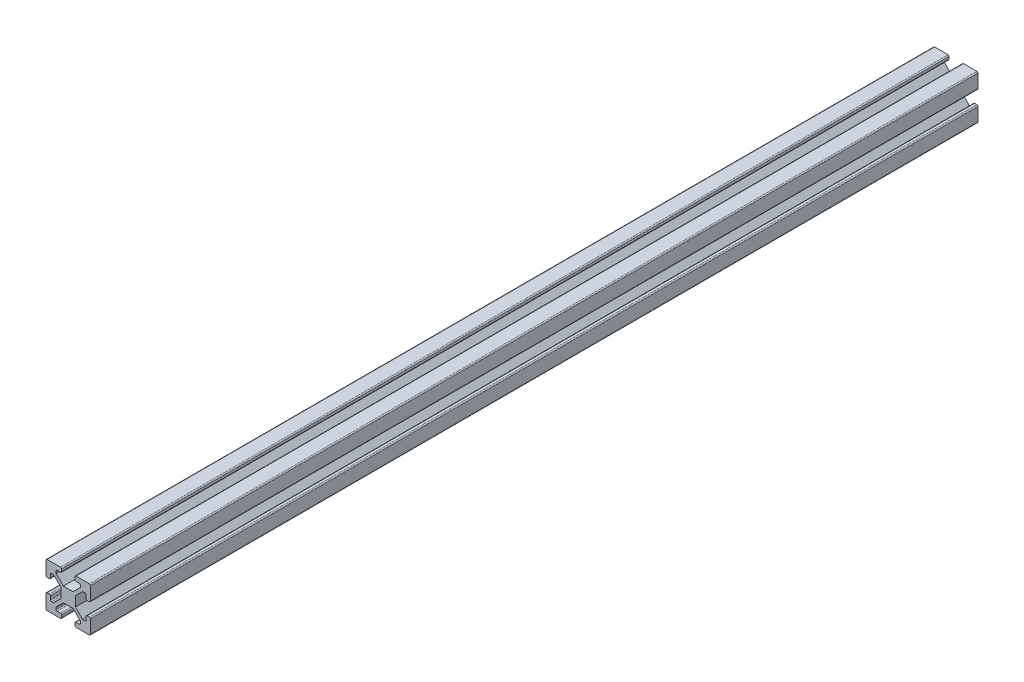
SolidWorks part; units mm, degrees
material "3.1645 (EN AW-2007)"
ref_plane "Front" through (0, 0, 0) normal (0, 0, 1) x (1, 0, 0)
ref_plane "Top" through (0, 0, 0) normal (0, 1, 0) x (1, 0, 0)
ref_plane "Right" through (0, 0, 0) normal (1, 0, 0) x (0, 0, -1)
sketch "草图1" plane through (0, 0, 0) normal (0, 0, 1) x (1, 0, 0)
  line L0 (6.5, 0) -> (0.5, 0)
  line L1 (20, -0.5) -> (20, -6.5)
  line L2 (19.5, -20) -> (13.5, -20)
  line L3 (20, -13.5) -> (20, -19.5)
  line L4 (13, -19.5) -> (13, -18.5)
  line L5 (13.5, -18) -> (15, -18)
  line L6 (15.5, -17.5) -> (15.5, -16.7791)
  line L7 (19.5, -7) -> (18.5, -7)
  line L8 (10, 0) -> (10, -26.2948) construction
  line L9 (18, -6.5) -> (18, -5)
  line L10 (17.5, -4.5) -> (16.7791, -4.5)
  line L11 (17.5, -15.5) -> (16.7791, -15.5)
  line L12 (18, -13.5) -> (18, -15)
  line L13 (19.5, -13) -> (18.5, -13)
  line L15 (0, -10) -> (20, -10) construction
  line L23 (4.5, -17.5) -> (4.5, -16.7791)
  line L24 (6.5, -18) -> (5, -18)
  line L25 (7, -19.5) -> (7, -18.5)
  line L27 (0.5, -20) -> (6.5, -20)
  line L29 (10, -20) -> (10, 6.2948) construction
  line L33 (0.5, -13) -> (1.5, -13)
  line L34 (2, -13.5) -> (2, -15)
  line L35 (2.5, -15.5) -> (3.2209, -15.5)
  line L36 (2.5, -4.5) -> (3.2209, -4.5)
  line L37 (2, -6.5) -> (2, -5)
  line L38 (0.5, -7) -> (1.5, -7)
  line L40 (7, -0.5) -> (7, -1.5)
  line L41 (6.5, -2) -> (5, -2)
  line L42 (4.5, -2.5) -> (4.5, -3.2209)
  line L43 (3.5745, -4.6464) -> (6.7416, -7.8136)
  line L44 (6.7416, -7.8136) -> (6.7416, -12.1864)
  line L45 (15.5, -2.5) -> (15.5, -3.2209)
  line L46 (13.5, -2) -> (15, -2)
  line L47 (13, -0.5) -> (13, -1.5)
  line L48 (19.5, 0) -> (13.5, 0)
  line L50 (10.3536, -10.3536) -> (20, -20) construction
  line L51 (4.6464, -3.5745) -> (7.8136, -6.7416)
  line L52 (7.8136, -6.7416) -> (12.1864, -6.7416)
  line L53 (0, -20) -> (9.6464, -10.3536) construction
  line L54 (15.3536, -3.5745) -> (12.1864, -6.7416)
  line L55 (13.2584, -7.8136) -> (13.2584, -12.1864)
  line L56 (16.4255, -4.6464) -> (13.2584, -7.8136)
  line L57 (10, 0) -> (10, -26.2948) construction
  line L58 (10, -20) -> (10, 6.2948) construction
  line L59 (16.4255, -15.3536) -> (13.2584, -12.1864)
  line L60 (15.3536, -16.4255) -> (12.3328, -13.4048)
  line L61 (8.0207, -13.2584) -> (11.9793, -13.2584)
  line L62 (4.6464, -16.4255) -> (7.6672, -13.4048)
  line L63 (3.5745, -15.3536) -> (6.7416, -12.1864)
  line L64 (0, -6.5) -> (0, -0.5)
  line L66 (0, -13.5) -> (0, -19.5)
  arc A0 (19.5, -7) -> (20, -6.5) centre (19.5, -6.5) ccw
  arc A1 (4.6464, -16.4255) -> (4.5, -16.7791) centre (5, -16.7791) ccw
  arc A2 (8.0207, -13.2584) -> (7.6672, -13.4048) centre (8.0207, -13.7584) ccw
  arc A3 (12.3328, -13.4048) -> (11.9793, -13.2584) centre (11.9793, -13.7584) ccw
  arc A4 (16.4255, -15.3536) -> (16.7791, -15.5) centre (16.7791, -15) ccw
  arc A5 (16.4255, -4.6464) -> (16.7791, -4.5) centre (16.7791, -5) cw
  arc A6 (15.3536, -16.4255) -> (15.5, -16.7791) centre (15, -16.7791) cw
  arc A7 (10.3536, -10.3536) -> (9.6464, -10.3536) centre (10, -10.7071) ccw construction
  arc A8 (15.3536, -3.5745) -> (15.5, -3.2209) centre (15, -3.2209) ccw
  arc A9 (3.5745, -15.3536) -> (3.2209, -15.5) centre (3.2209, -15) cw
  arc A10 (3.5745, -4.6464) -> (3.2209, -4.5) centre (3.2209, -5) ccw
  arc A11 (0.5, -7) -> (0, -6.5) centre (0.5, -6.5) cw
  arc A12 (2, -6.5) -> (1.5, -7) centre (1.5, -6.5) cw
  arc A13 (4.6464, -3.5745) -> (4.5, -3.2209) centre (5, -3.2209) cw
  arc A14 (2.5, -4.5) -> (2, -5) centre (2.5, -5) ccw
  arc A15 (2, -15) -> (2.5, -15.5) centre (2.5, -15) ccw
  arc A16 (1.5, -13) -> (2, -13.5) centre (1.5, -13.5) cw
  arc A17 (0.5, -13) -> (0, -13.5) centre (0.5, -13.5) ccw
  arc A18 (19.5, -13) -> (20, -13.5) centre (19.5, -13.5) cw
  arc A19 (13.5, 0) -> (13, -0.5) centre (13.5, -0.5) ccw
  arc A20 (13, -1.5) -> (13.5, -2) centre (13.5, -1.5) ccw
  arc A21 (15, -2) -> (15.5, -2.5) centre (15, -2.5) cw
  arc A22 (18, -13.5) -> (18.5, -13) centre (18.5, -13.5) cw
  arc A23 (4.5, -2.5) -> (5, -2) centre (5, -2.5) cw
  arc A24 (6.5, -2) -> (7, -1.5) centre (6.5, -1.5) ccw
  arc A25 (7, -0.5) -> (6.5, 0) centre (6.5, -0.5) ccw
  arc A26 (6.5, -18) -> (7, -18.5) centre (6.5, -18.5) cw
  arc A27 (4.5, -17.5) -> (5, -18) centre (5, -17.5) ccw
  arc A28 (17.5, -15.5) -> (18, -15) centre (17.5, -15) ccw
  arc A29 (15, -18) -> (15.5, -17.5) centre (15, -17.5) ccw
  arc A30 (13, -18.5) -> (13.5, -18) centre (13.5, -18.5) cw
  arc A31 (18, -5) -> (17.5, -4.5) centre (17.5, -5) ccw
  arc A32 (18.5, -7) -> (18, -6.5) centre (18.5, -6.5) cw
  arc A33 (19.5, 0) -> (20, -0.5) centre (19.5, -0.5) cw
  arc A34 (0.5, 0) -> (0, -0.5) centre (0.5, -0.5) ccw
  arc A35 (7, -19.5) -> (6.5, -20) centre (6.5, -19.5) cw
  arc A36 (13.5, -20) -> (13, -19.5) centre (13.5, -19.5) cw
  arc A37 (0.5, -20) -> (0, -19.5) centre (0.5, -19.5) cw
  arc A38 (20, -19.5) -> (19.5, -20) centre (19.5, -19.5) cw
  point P28 (4.5, -16.572)
  point P50 (10, -6.7416)
  point P56 (13.2584, -10)
  point P61 (6.7416, -10)
  point P62 (10, -13.2584)
  point P63 (7.8136, -13.2584)
  point P66 (12.1864, -13.2584)
  point P69 (16.572, -15.5)
  point P72 (16.572, -4.5)
  point P75 (15.5, -16.572)
  point P78 (10, -10)
  point P81 (15.5, -3.428)
  point P84 (3.428, -15.5)
  point P87 (3.428, -4.5)
  point P94 (4.5, -3.428)
  point P107 (13, 0)
  point P110 (13, -2)
  point P113 (15.5, -2)
  point P118 (4.5, -2)
  point P121 (7, -2)
  point P124 (7, 0)
  point P127 (7, -18)
  point P130 (4.5, -18)
  point P135 (15.5, -18)
  point P138 (13, -18)
  point P145 (20, 0)
  point P148 (0, 0)
  point P151 (7, -20)
  point P154 (13, -20)
  dimension "D1" = 6.7416
  dimension "D2" = 6
  dimension "D3" = 2
extrude "凸台-拉伸1" add sketch "草图1" along normal blind 400
